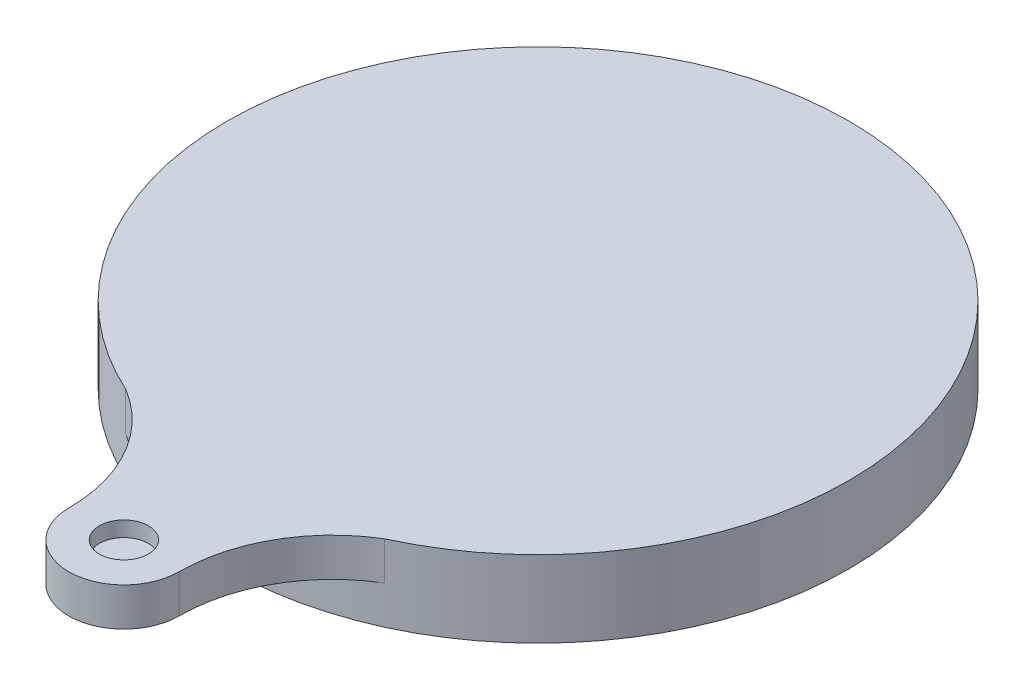
SolidWorks part; units mm, degrees
ref_plane "Front Plane" through (0, 0, 0) normal (0, 0, 1) x (1, 0, 0)
ref_plane "Top Plane" through (0, 0, 0) normal (0, 1, 0) x (1, 0, 0)
ref_plane "Right Plane" through (0, 0, 0) normal (1, 0, 0) x (0, 0, -1)
sketch "Sketch1" plane through (0, 0, 0) normal (0, 1, 0) x (1, 0, 0)
  circle A0 centre (0, 0) radius 203
extrude "Boss-Extrude1" add sketch "Sketch1" along normal blind 50
sketch "Sketch2" plane through (0, 50, 0) normal (0, 1, 0) x (1, 0, 0)
  line L0 (0, -203) -> (0, -255.5722) construction
  line L1 (67.4152, -270.2972) -> (-52.5909, -270.2972) construction
  line L2 (0, -270.2972) -> (0, -279.918) construction
  circle A0 centre (0, 0) radius 203 construction
  arc A1 (-36, -270.2972) -> (36, -270.2972) centre (0, -270.2972) ccw
  arc A2 (-36, -270.2972) -> (-84.507, -184.574) centre (-136, -270.2972) ccw
  arc A3 (36, -270.2972) -> (84.507, -184.574) centre (136, -270.2972) cw
  circle A5 centre (0, 0) radius 203
  arc A6 (-84.507, -184.574) -> (84.507, -184.574) centre (0, 0) ccw
  point P16 (-48.9675, -221.0494)
  dimension "D1" = 169.014
  dimension "D3" = 36
  dimension "D2" = 100
  dimension "D4" = 0
extrude "Boss-Extrude2" add sketch "Sketch2" against normal blind 25
sketch "Sketch3" plane through (0, 50, 0) normal (0, 1, 0) x (1, 0, 0)
  circle A0 centre (0, -270.2972) radius 16
extrude "Cut-Extrude1" cut sketch "Sketch3" against normal blind 10
